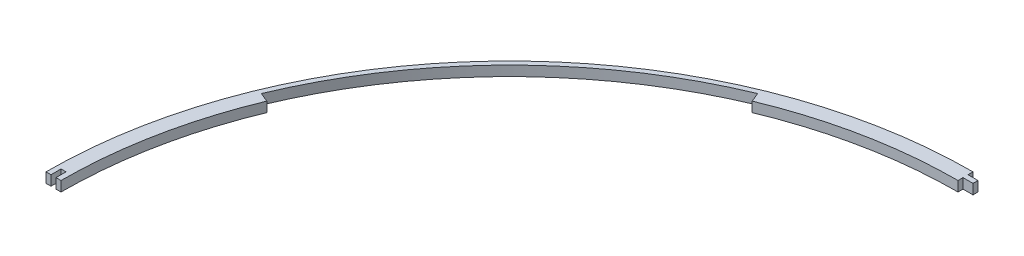
SolidWorks part; units mm, degrees
ref_plane "Front Plane" through (0, 0, 0) normal (0, 0, 1) x (1, 0, 0)
ref_plane "Top Plane" through (0, 0, 0) normal (0, 1, 0) x (1, 0, 0)
ref_plane "Right Plane" through (0, 0, 0) normal (1, 0, 0) x (0, 0, -1)
sketch "Sketch1" plane through (0, 0, 0) normal (0, 1, 0) x (1, 0, 0)
  line L0 (0, 0) -> (0, 284.861) construction
  line L1 (0, 0) -> (-284.861, 0) construction
  line L2 (0, 284.861) -> (0, 288.036)
  line L3 (0, 288.036) -> (6.35, 288.036)
  line L4 (6.35, 288.036) -> (6.35, 291.211)
  line L5 (6.35, 291.211) -> (0, 291.211)
  line L6 (0, 291.211) -> (0, 294.386)
  line L7 (-284.861, 0) -> (-288.036, 0)
  line L8 (-291.211, 0) -> (-291.211, 6.35)
  line L9 (-291.211, 6.35) -> (-288.036, 6.35)
  line L10 (-288.036, 6.35) -> (-288.036, 0)
  line L11 (-291.211, 0) -> (-294.386, 0)
  line L12 (0, 281.686) -> (0, 284.861)
  line L13 (0, 0) -> (-107.7966, 260.2439) construction
  line L14 (-107.7966, 260.2439) -> (-109.0116, 263.1772) construction
  line L15 (-109.0116, 263.1772) -> (-112.6566, 271.9772)
  line L16 (0, 0) -> (-260.2439, 107.7966) construction
  line L17 (-260.2439, 107.7966) -> (-263.1772, 109.0116) construction
  line L18 (-263.1772, 109.0116) -> (-271.9772, 112.6566)
  arc A0 (0, 294.386) -> (-294.386, 0) centre (0, 0) ccw
  arc A1 (-111.4416, 269.0439) -> (-269.0439, 111.4416) centre (0, 0) ccw
  arc A2 (0, 284.861) -> (-109.0116, 263.1772) centre (0, 0) ccw
  arc A3 (0, 281.686) -> (-281.686, 0) centre (0, 0) ccw
  arc A4 (-263.1772, 109.0116) -> (-284.861, 0) centre (0, 0) ccw
  dimension "D1" = 588.772
  dimension "D2" = 9.525
  dimension "D3" = 3.175
  dimension "D6" = 3.175
  dimension "D4" = 6.35
  dimension "D5" = 6.35
  dimension "D7" = 22.5
  dimension "D8" = 22.5
extrude "Boss-Extrude1" add sketch "Sketch1" along normal blind 6.35 contours A2 L2 L3 L4 L5 L6 A0 L15 | A1 L15 A0 L18 | A4 L18 A0 L11 L8 L9 L10 L7
